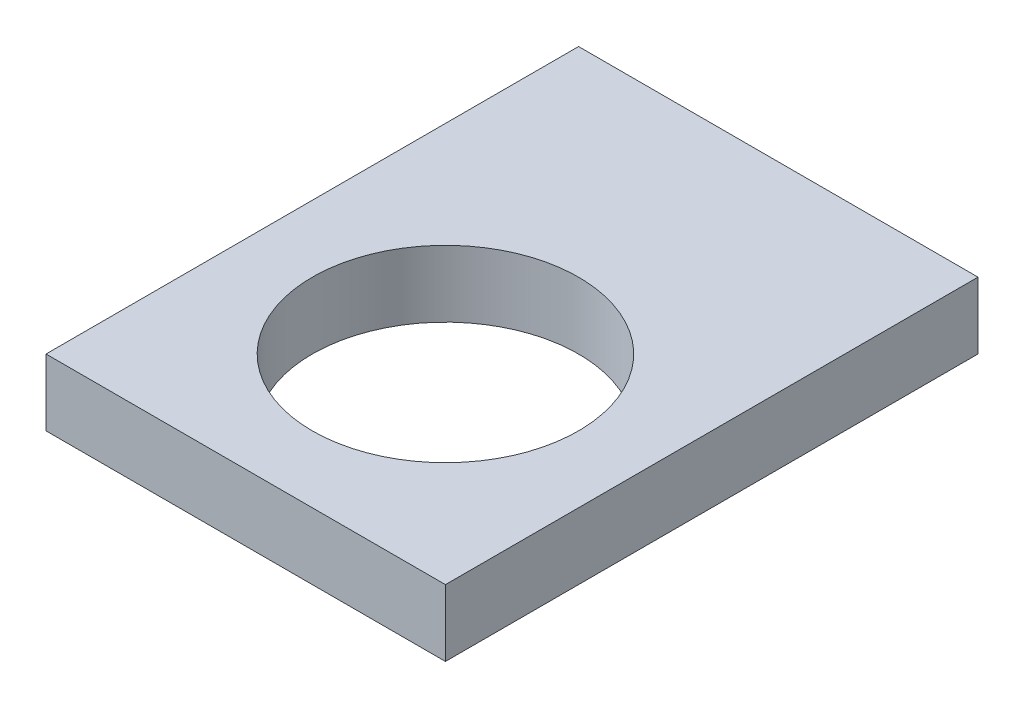
SolidWorks part; units mm, degrees
ref_plane "Plan de face" through (0, 0, 0) normal (0, 0, 1) x (1, 0, 0)
ref_plane "Plan de dessus" through (0, 0, 0) normal (0, 1, 0) x (1, 0, 0)
ref_plane "Plan de droite" through (0, 0, 0) normal (1, 0, 0) x (0, 0, -1)
sketch "Esquisse1" plane through (0, 0, 0) normal (0, 1, 0) x (1, 0, 0)
  line L1 (-15, -20) -> (15, -20)
  line L2 (-15, -20) -> (-15, 20)
  line L3 (-15, 20) -> (15, 20)
  line L4 (15, -20) -> (15, 20)
  line L5 (-15, -20) -> (15, 20) construction
  line L6 (-15, 20) -> (15, -20) construction
  point P0 (0, 0)
  dimension "D1" = 40
  dimension "D2" = 30
extrude "Boss.-Extru.1" add sketch "Esquisse1" along normal blind 5
sketch "Esquisse3" plane through (0, 5, 0) normal (0, 1, 0) x (1, 0, 0)
  line L1 (-15, -20) -> (15, -20) construction
  circle A1 centre (0, -5) radius 10
  dimension "D1" = 15
  dimension "D2" = 20
extrude "Enlèv. mat.-Extru.1" cut sketch "Esquisse3" against normal through all
